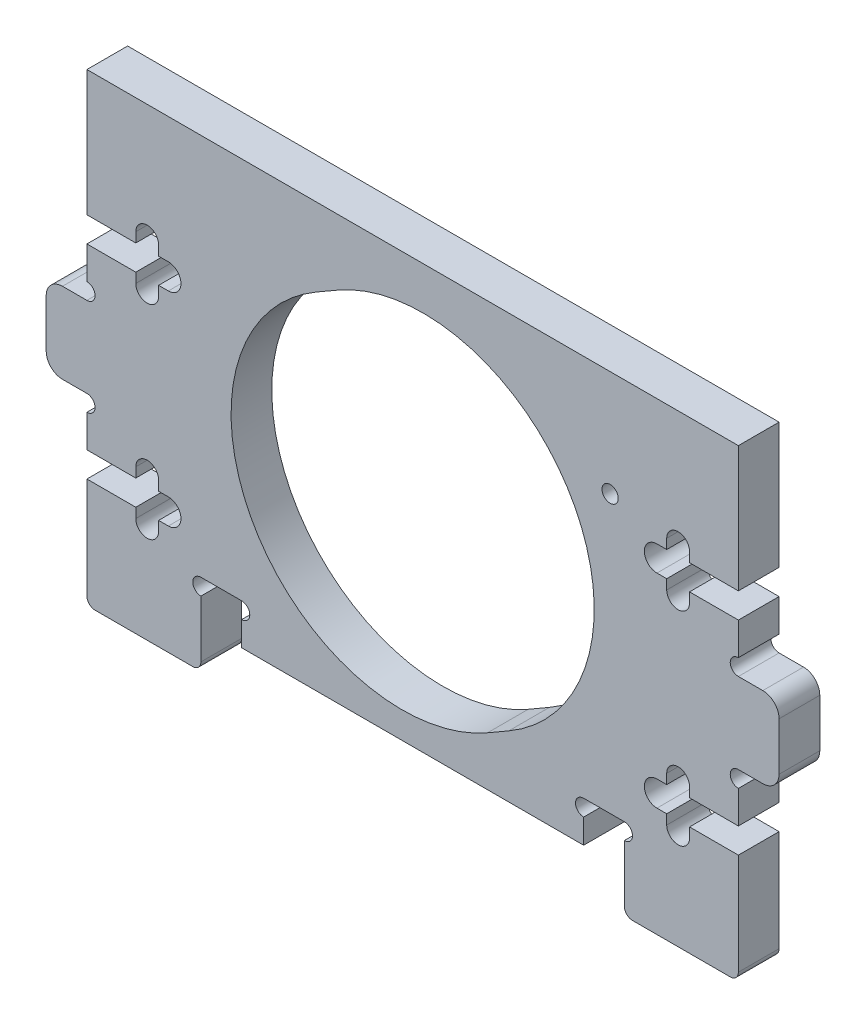
SolidWorks part; units mm, degrees
ref_plane "정면" through (0, 0, 0) normal (0, 0, 1) x (1, 0, 0)
ref_plane "윗면" through (0, 0, 0) normal (0, 1, 0) x (1, 0, 0)
ref_plane "우측면" through (0, 0, 0) normal (1, 0, 0) x (0, 0, -1)
sketch "스케치1" plane through (0, 0, 0) normal (0, 0, 1) x (1, 0, 0)
  line L1 (-50, 17.4622) -> (30, 17.4622)
  line L2 (-50, 17.4622) -> (-50, -34.5378)
  line L3 (-50, -34.5378) -> (30, -34.5378)
  line L4 (30, 17.4622) -> (30, -34.5378)
  dimension "D1" = 80
  dimension "D2" = 52
extrude "보스-돌출1" add sketch "스케치1" along normal blind 5
sketch "스케치2" plane through (0, 0, 5) normal (0, 0, 1) x (1, 0, 0)
  line L0 (30, -34.5378) -> (30, 17.4622) construction
  line L1 (30, 7.4622) -> (35, 7.4622)
  line L2 (30, 7.4622) -> (30, -2.5378)
  line L3 (30, -2.5378) -> (35, -2.5378)
  line L4 (35, 7.4622) -> (35, -2.5378)
  line L5 (35, -2.5378) -> (35, -14.5378) construction
  line L6 (30, -14.5378) -> (35, -14.5378)
  line L7 (30, -14.5378) -> (30, -24.5378)
  line L8 (30, -24.5378) -> (35, -24.5378)
  line L9 (35, -14.5378) -> (35, -24.5378)
  line L10 (30, 17.4622) -> (-50, 17.4622) construction
  line L11 (-50, -34.5378) -> (30, -34.5378) construction
  line L12 (-10, 17.4622) -> (-10, -34.5378) construction
  line L13 (-55, -14.5378) -> (-55, -24.5378)
  line L14 (-50, -24.5378) -> (-55, -24.5378)
  line L15 (-50, -14.5378) -> (-50, -24.5378)
  line L16 (-50, -14.5378) -> (-55, -14.5378)
  line L17 (-55, 7.4622) -> (-55, -2.5378)
  line L18 (-50, -2.5378) -> (-55, -2.5378)
  line L19 (-50, 7.4622) -> (-50, -2.5378)
  line L20 (-50, 7.4622) -> (-55, 7.4622)
  dimension "D1" = 5
  dimension "D2" = 10
  dimension "D3" = 10
  dimension "D4" = 10
  dimension "D5" = 10
extrude "보스-돌출2" [suppressed] add sketch "스케치2" against normal blind 5
sketch "스케치5" [suppressed] plane through (0, 0, 5) normal (0, 0, 1) x (1, 0, 0)
  line L0 (30, 17.4622) -> (35, 17.4622) construction
  line L1 (35, 17.4622) -> (35, 7.4622) construction
  line L2 (-2.5, 17.4622) -> (-2.5, -34.5378) construction
  line L3 (35, 17.4622) -> (80, 17.4622)
  line L4 (35, 17.4622) -> (35, -34.5378)
  line L5 (35, -34.5378) -> (80, -34.5378)
  line L6 (80, 17.4622) -> (80, -34.5378)
  line L7 (30, 17.4622) -> (-35, 17.4622) construction
  line L8 (-35, -34.5378) -> (30, -34.5378) construction
  line L9 (-40, 17.4622) -> (-40, 7.4622) construction
  line L10 (-35, 17.4622) -> (-40, 17.4622) construction
  line L11 (-85, 17.4622) -> (-85, -34.5378)
  line L12 (-40, -34.5378) -> (-85, -34.5378)
  line L13 (-40, 17.4622) -> (-40, -34.5378)
  line L14 (-40, 17.4622) -> (-85, 17.4622)
  dimension "D1" = 82.5
extrude "보스-돌출3" [suppressed] add sketch "스케치5" against normal blind 5
sketch "스케치6" [suppressed] plane through (0, 0, 5) normal (0, 0, 1) x (1, 0, 0)
  line L0 (55, 17.4622) -> (55, -7.5378) construction
  line L1 (75, 17.4622) -> (35, 17.4622) construction
  line L2 (55, -7.5378) -> (75, -7.5378) construction
  line L3 (75, -34.5378) -> (75, 17.4622) construction
  line L4 (-2.5, 17.4622) -> (-2.5, -34.5378) construction
  line L5 (39.35, -23.1878) -> (70.65, -23.1878) construction
  line L6 (39.35, -23.1878) -> (39.35, 8.1122) construction
  line L7 (39.35, 8.1122) -> (70.65, 8.1122) construction
  line L8 (70.65, -23.1878) -> (70.65, 8.1122) construction
  line L9 (39.35, -23.1878) -> (70.65, 8.1122) construction
  line L10 (39.35, 8.1122) -> (70.65, -23.1878) construction
  line L11 (30, 17.4622) -> (-35, 17.4622) construction
  line L12 (-35, -34.5378) -> (30, -34.5378) construction
  line L13 (-44.35, 8.1122) -> (-75.65, -23.1878) construction
  line L14 (-44.35, -23.1878) -> (-75.65, 8.1122) construction
  line L15 (-75.65, -23.1878) -> (-75.65, 8.1122) construction
  line L16 (-44.35, 8.1122) -> (-75.65, 8.1122) construction
  line L17 (-44.35, -23.1878) -> (-44.35, 8.1122) construction
  line L18 (-44.35, -23.1878) -> (-75.65, -23.1878) construction
  line L19 (-60, -7.5378) -> (-80, -7.5378) construction
  line L20 (-60, 17.4622) -> (-60, -7.5378) construction
  circle A0 centre (70.65, 8.1122) radius 1.75
  circle A1 centre (70.65, -23.1878) radius 1.75
  circle A2 centre (39.35, -23.1878) radius 1.75
  circle A3 centre (39.35, 8.1122) radius 1.75
  circle A4 centre (55, -7.5378) radius 11.5
  circle A5 centre (-60, -7.5378) radius 11.5
  circle A6 centre (-44.35, 8.1122) radius 1.75
  circle A7 centre (-44.35, -23.1878) radius 1.75
  circle A8 centre (-75.65, -23.1878) radius 1.75
  circle A9 centre (-75.65, 8.1122) radius 1.75
  dimension "D3" = 3.5
  dimension "D4" = 23
  dimension "D1" = 31.3
  dimension "D2" = 31.3
  dimension "D5" = 20
  dimension "D6" = 25
extrude "컷-돌출2" [suppressed] cut sketch "스케치6" against normal blind 5
sketch "스케치7" plane through (0, 0, 0) normal (0, 0, -1) x (-1, 0, 0)
  line L0 (-30, -34.5378) -> (-30, 17.4622) construction
  line L1 (-30, 2.0122) -> (-24, 2.0122)
  line L2 (-30, 2.0122) -> (-30, -1.0878)
  line L3 (-30, -1.0878) -> (-24, -1.0878)
  line L4 (-20, 2.0122) -> (-20, -1.0878) construction
  line L5 (-21.2, -1.0878) -> (-20, -1.0878)
  line L6 (-24, 2.0122) -> (-24, 3.2122)
  line L7 (-24, 3.2122) -> (-21.2, 3.2122) construction
  line L8 (-21.2, 3.2122) -> (-21.2, 2.0122)
  line L9 (-21.2, -1.0878) -> (-21.2, -2.2878)
  line L10 (-21.2, -2.2878) -> (-24, -2.2878) construction
  line L11 (-21.2, 2.0122) -> (-20, 2.0122)
  line L12 (-24, -2.2878) -> (-24, -1.0878)
  line L13 (-30, -22.9878) -> (-24, -22.9878)
  line L14 (-24, 2.0122) -> (-24, -1.0878) construction
  line L15 (-21.2, 2.0122) -> (-21.2, -1.0878) construction
  line L16 (-24, -1.0878) -> (-21.2, -1.0878) construction
  line L17 (-21.2, 2.0122) -> (-24, 2.0122) construction
  line L18 (-30, -22.9878) -> (-30, -26.0878)
  line L19 (-30, -26.0878) -> (-24, -26.0878)
  line L20 (-20, -22.9878) -> (-20, -26.0878) construction
  line L21 (-21.2, -26.0878) -> (-20, -26.0878)
  line L22 (-24, -22.9878) -> (-24, -21.7878)
  line L23 (-24, -21.7878) -> (-21.2, -21.7878) construction
  line L24 (-21.2, -21.7878) -> (-21.2, -22.9878)
  line L25 (-21.2, -26.0878) -> (-21.2, -27.2878)
  line L26 (-21.2, -27.2878) -> (-24, -27.2878) construction
  line L27 (-21.2, -22.9878) -> (-20, -22.9878)
  line L28 (-24, -27.2878) -> (-24, -26.0878)
  line L29 (-24, -22.9878) -> (-24, -26.0878) construction
  line L30 (-21.2, -22.9878) -> (-21.2, -26.0878) construction
  line L31 (-24, -26.0878) -> (-21.2, -26.0878) construction
  line L32 (-21.2, -22.9878) -> (-24, -22.9878) construction
  line L33 (-20, -24.5378) -> (-13.8728, -24.5378) construction
  line L34 (-13.8728, -24.5378) -> (-13.8728, 0.4622) construction
  line L35 (-13.8728, 0.4622) -> (-20, 0.4622) construction
  line L36 (50, -34.5378) -> (-30, -34.5378) construction
  line L37 (10, 17.4622) -> (10, -34.5378) construction
  line L38 (-30, 17.4622) -> (50, 17.4622) construction
  line L39 (33.8728, 0.4622) -> (40, 0.4622) construction
  line L40 (33.8728, -24.5378) -> (33.8728, 0.4622) construction
  line L41 (40, -24.5378) -> (33.8728, -24.5378) construction
  line L42 (41.2, -22.9878) -> (44, -22.9878) construction
  line L43 (44, -26.0878) -> (41.2, -26.0878) construction
  line L44 (41.2, -22.9878) -> (41.2, -26.0878) construction
  line L45 (44, -22.9878) -> (44, -26.0878) construction
  line L46 (41.2, -27.2878) -> (44, -27.2878) construction
  line L47 (44, -21.7878) -> (41.2, -21.7878) construction
  line L48 (40, -22.9878) -> (40, -26.0878) construction
  line L49 (41.2, 2.0122) -> (44, 2.0122) construction
  line L50 (44, -1.0878) -> (41.2, -1.0878) construction
  line L51 (41.2, 2.0122) -> (41.2, -1.0878) construction
  line L52 (44, 2.0122) -> (44, -1.0878) construction
  line L53 (41.2, -2.2878) -> (44, -2.2878) construction
  line L54 (44, 3.2122) -> (41.2, 3.2122) construction
  line L55 (40, 2.0122) -> (40, -1.0878) construction
  line L56 (44, -27.2878) -> (44, -26.0878)
  line L57 (41.2, -22.9878) -> (40, -22.9878)
  line L58 (41.2, -26.0878) -> (41.2, -27.2878)
  line L59 (41.2, -21.7878) -> (41.2, -22.9878)
  line L60 (44, -22.9878) -> (44, -21.7878)
  line L61 (41.2, -26.0878) -> (40, -26.0878)
  line L62 (50, -26.0878) -> (44, -26.0878)
  line L63 (50, -22.9878) -> (50, -26.0878)
  line L64 (50, -22.9878) -> (44, -22.9878)
  line L65 (44, -2.2878) -> (44, -1.0878)
  line L66 (41.2, 2.0122) -> (40, 2.0122)
  line L67 (41.2, -1.0878) -> (41.2, -2.2878)
  line L68 (41.2, 3.2122) -> (41.2, 2.0122)
  line L69 (44, 2.0122) -> (44, 3.2122)
  line L70 (41.2, -1.0878) -> (40, -1.0878)
  line L71 (50, -1.0878) -> (44, -1.0878)
  line L72 (50, 2.0122) -> (50, -1.0878)
  line L73 (50, 2.0122) -> (44, 2.0122)
  arc A0 (-21.2, 3.2122) -> (-24, 3.2122) centre (-22.6, 3.2122) ccw
  arc A1 (-24, -2.2878) -> (-21.2, -2.2878) centre (-22.6, -2.2878) ccw
  arc A2 (-20, -1.0878) -> (-20, 2.0122) centre (-20, 0.4622) ccw
  arc A3 (-21.2, -21.7878) -> (-24, -21.7878) centre (-22.6, -21.7878) ccw
  arc A4 (-24, -27.2878) -> (-21.2, -27.2878) centre (-22.6, -27.2878) ccw
  arc A5 (-20, -26.0878) -> (-20, -22.9878) centre (-20, -24.5378) ccw
  arc A6 (40, -26.0878) -> (40, -22.9878) centre (40, -24.5378) cw
  arc A7 (44, -27.2878) -> (41.2, -27.2878) centre (42.6, -27.2878) cw
  arc A8 (41.2, -21.7878) -> (44, -21.7878) centre (42.6, -21.7878) cw
  arc A9 (40, -1.0878) -> (40, 2.0122) centre (40, 0.4622) cw
  arc A10 (44, -2.2878) -> (41.2, -2.2878) centre (42.6, -2.2878) cw
  arc A11 (41.2, 3.2122) -> (44, 3.2122) centre (42.6, 3.2122) cw
  dimension "D6" = 10
  dimension "D1" = 5.5
  dimension "D2" = 3.1
  dimension "D3" = 3.1
  dimension "D4" = 10
  dimension "D5" = 2.8
  dimension "D7" = 5.5
  dimension "D8" = 2.8
  dimension "D9" = 10
  dimension "D10" = 25
extrude "컷-돌출3" cut sketch "스케치7" against normal blind 10
sketch "스케치8" plane through (0, 0, 0) normal (0, 0, -1) x (-1, 0, 0)
  line L0 (50, -1.0878) -> (50, -22.9878) construction
  line L3 (50, -34.5378) -> (-30, -34.5378) construction
  line L4 (8.701, -8.7878) -> (11.299, -10.2878) construction
  line L5 (19.201, 9.3988) -> (21.799, 7.8988)
  line L6 (-1.799, -26.9743) -> (0.799, -28.4743)
  arc A0 (19.201, 9.3988) -> (-1.799, -26.9743) centre (8.701, -8.7878) ccw
  arc A1 (0.799, -28.4743) -> (21.799, 7.8988) centre (11.299, -10.2878) ccw
  point P9 (10, -9.5378)
  dimension "D1" = 21
  dimension "D2" = 30
  dimension "D3" = 3
  dimension "D4" = 40
  dimension "D5" = 25
extrude "컷-돌출4" cut sketch "스케치8" against normal blind 10
sketch "스케치9" plane through (0, 0, 0) normal (0, 0, -1) x (-1, 0, 0)
  line L0 (10, -9.5378) -> (-14.2487, 4.4622) construction
  line L18 (10, -9.5378) -> (10, 17.4622) construction
  line L19 (-30, 17.4622) -> (50, 17.4622) construction
  circle A1 centre (-14.2487, 4.4622) radius 1
  point P14 (10, -9.5378)
  dimension "D2" = 28
  dimension "D3" = 2
  dimension "D1" = 60
extrude "컷-돌출5" cut sketch "스케치9" against normal blind 10
sketch "스케치10" plane through (0, 0, 5) normal (0, 0, 1) x (1, 0, 0)
  line L0 (-50, -34.5378) -> (30, -34.5378) construction
  line L1 (16, -29.5378) -> (11, -29.5378)
  line L2 (16, -29.5378) -> (16, -34.5378)
  line L3 (16, -34.5378) -> (11, -34.5378)
  line L4 (11, -29.5378) -> (11, -34.5378)
  line L5 (11, -29.5378) -> (11, -34.5378) construction
  line L6 (-36, -29.5378) -> (-36, -34.5378) construction
  line L7 (-31, -29.5378) -> (-36, -29.5378)
  line L8 (-31, -29.5378) -> (-31, -34.5378)
  line L9 (-31, -34.5378) -> (-36, -34.5378)
  line L10 (-36, -29.5378) -> (-36, -34.5378)
extrude "컷-돌출6" cut sketch "스케치10" against normal blind 10
sketch "스케치11" plane through (0, 0, 0) normal (0, 0, -1) x (-1, 0, 0)
  line L0 (-11, -29.5378) -> (-11, -34.5378) construction
  line L1 (-16, -34.5378) -> (-16, -29.5378) construction
  line L2 (31, -34.5378) -> (31, -29.5378) construction
  line L3 (36, -29.5378) -> (36, -34.5378) construction
  circle A0 centre (-11, -30.5378) radius 1
  circle A1 centre (-16, -30.5378) radius 1
  circle A2 centre (31, -30.5378) radius 1
  circle A3 centre (36, -30.5378) radius 1
  dimension "D1" = 2
extrude "컷-돌출7" cut sketch "스케치11" against normal blind 10
sketch "스케치12" plane through (0, 0, 0) normal (0, 0, -1) x (-1, 0, 0)
  line L0 (50, -1.0878) -> (50, -22.9878) construction
  line L1 (50, -7.0878) -> (55, -7.0878)
  line L2 (50, -7.0878) -> (50, -16.9878)
  line L3 (50, -16.9878) -> (55, -16.9878)
  line L4 (55, -7.0878) -> (55, -16.9878)
  line L5 (55, -34.5378) -> (55, -16.9878) construction
  line L6 (44, -1.0878) -> (50, -1.0878) construction
  line L7 (50, -22.9878) -> (44, -22.9878) construction
  line L8 (10, 17.4622) -> (10, -34.5378) construction
  line L9 (-30, 17.4622) -> (50, 17.4622) construction
  line L10 (31, -34.5378) -> (-11, -34.5378) construction
  line L11 (-35, -7.0878) -> (-35, -16.9878)
  line L12 (-30, -16.9878) -> (-35, -16.9878)
  line L13 (-30, -7.0878) -> (-30, -16.9878)
  line L14 (-30, -7.0878) -> (-35, -7.0878)
  dimension "D1" = 6
  dimension "D2" = 6
extrude "보스-돌출4" add sketch "스케치12" against normal blind 5
sketch "스케치13" plane through (0, 0, 0) normal (0, 0, -1) x (-1, 0, 0)
  line L0 (50, -1.0878) -> (50, -7.0878) construction
  line L3 (50, -16.9878) -> (50, -22.9878) construction
  line L4 (-30, -34.5378) -> (-30, -16.9878) construction
  line L5 (-30, -22.9878) -> (-30, -16.9878) construction
  circle A0 centre (50, -6.0878) radius 1
  circle A1 centre (50, -17.9878) radius 1
  circle A2 centre (-30, -6.0878) radius 1
  circle A3 centre (-30, -17.9878) radius 1
  dimension "D1" = 2
extrude "컷-돌출8" cut sketch "스케치13" against normal blind 5
fillet "필렛2" radius 2 4 edges at (35, -16.9878, 2.5) (35, -7.0878, 2.5) (-55, -16.9878, 2.5) (-55, -7.0878, 2.5)
sketch "스케치14" plane through (0, 0, 0) normal (0, 0, -1) x (-1, 0, 0)
  line L1 (50, -34.5378) -> (36, -34.5378)
  line L2 (50, -34.5378) -> (50, -39.5378)
  line L3 (50, -39.5378) -> (36, -39.5378)
  line L4 (36, -34.5378) -> (36, -39.5378)
  line L5 (-16, -34.5378) -> (-30, -34.5378)
  line L6 (-16, -34.5378) -> (-16, -39.5378)
  line L7 (-16, -39.5378) -> (-30, -39.5378)
  line L8 (-30, -34.5378) -> (-30, -39.5378)
  dimension "D1" = 5
extrude "보스-돌출5" add sketch "스케치14" against normal blind 5
fillet "필렛3" radius 1 4 edges at (30, -39.5378, 2.5) (-36, -39.5378, 2.5) (-50, -39.5378, 2.5) (16, -39.5378, 2.5)
